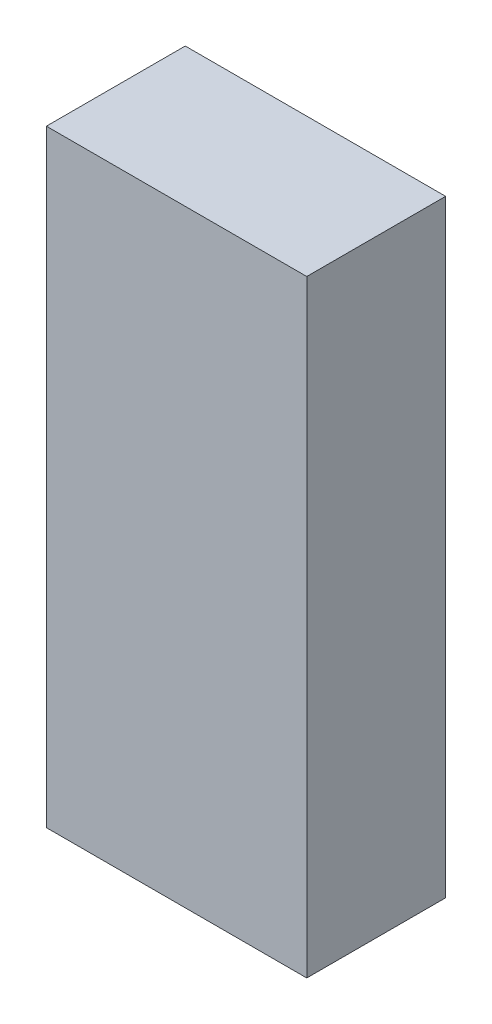
SolidWorks part; units mm, degrees
ref_plane "Front Plane" through (0, 0, 0) normal (0, 0, 1) x (1, 0, 0)
ref_plane "Top Plane" through (0, 0, 0) normal (0, 1, 0) x (1, 0, 0)
ref_plane "Right Plane" through (0, 0, 0) normal (1, 0, 0) x (0, 0, -1)
sketch "Sketch1" plane through (0, 0, 0) normal (0, 0, 1) x (1, 0, 0)
  line L0 (0, -17.5) -> (0, 0) construction
  line L1 (-3.75, -17.5) -> (3.75, -17.5)
  line L2 (-3.75, -17.5) -> (-3.75, 0)
  line L3 (-3.75, 0) -> (3.75, 0)
  line L4 (3.75, -17.5) -> (3.75, 0)
  line L5 (0, -12) -> (0, -28) construction
  line L7 (-15.4, 0) -> (15.4, 0) construction
  dimension "D1" = 7.5
  dimension "D2" = 17.5
extrude "Boss-Extrude1" add sketch "Sketch1" along normal blind 4
